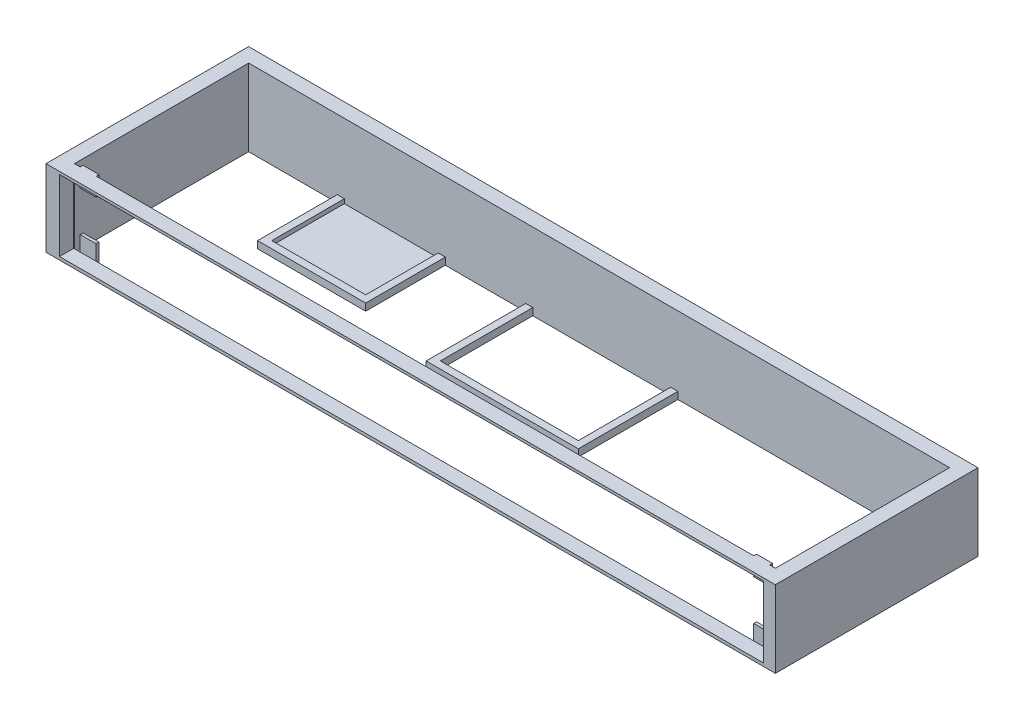
SolidWorks part; units mm, degrees
material "PLA"
ref_plane "Front Plane" through (0, 0, 0) normal (0, 0, 1) x (1, 0, 0)
ref_plane "Top Plane" through (0, 0, 0) normal (0, 1, 0) x (1, 0, 0)
ref_plane "Right Plane" through (0, 0, 0) normal (1, 0, 0) x (0, 0, -1)
sketch "Sketch2" plane through (0, 0, 0) normal (0, 1, 0) x (1, 0, 0)
  line L0 (0, -55) -> (0, 55) construction
  line L1 (-256.4, 71.4) -> (256.4, 71.4)
  line L2 (-256.4, 71.4) -> (-256.4, -71.08)
  line L3 (-256.4, -71.08) -> (256.4, -71.08)
  line L4 (256.4, 71.4) -> (256.4, -71.08)
  line L5 (-55, 0) -> (55, 0) construction
  dimension "D1" = 142.48
  dimension "D2" = 512.8
  dimension "D3" = 256.4
  dimension "D4" = 71.4
extrude "Extrude-Thin1" add sketch "Sketch2" along normal blind 54 thin contours L4 L3 L2 L1
sketch "Sketch3" plane through (0, 0, 71.08) normal (0, 0, 1) x (1, 0, 0)
  line L1 (-246.9323, 52.1414) -> (248.0677, 52.1414)
  line L2 (-246.9323, 52.1414) -> (-246.9323, 2.1414)
  line L3 (-246.9323, 2.1414) -> (248.0677, 2.1414)
  line L4 (248.0677, 52.1414) -> (248.0677, 2.1414)
  dimension "D1" = 50
  dimension "D2" = 495
extrude "Cut-Extrude1" cut sketch "Sketch3" against normal blind 10 contours L1 L4 L3 L2
sketch "Sketch4" plane through (0, 0, 61.08) normal (0, 0, -1) x (-1, 0, 0)
  line L0 (246.4, 54) -> (-246.4, 54) construction
  line L1 (242.3627, 54) -> (231.1637, 54)
  line L2 (242.3627, 54) -> (242.3627, 41.1714)
  line L3 (242.3627, 41.1714) -> (231.1637, 41.1714)
  line L4 (231.1637, 54) -> (231.1637, 41.1714)
extrude "Boss-Extrude1" add sketch "Sketch4" along normal blind 2
mirror "Mirror1" about plane through (0, 0, 0) normal (1, 0, 0) of "Boss-Extrude1"
ref_plane "Plane1" through (0, 27, 0) normal (0, 1, 0) x (1, 0, 0)
mirror "Mirror2" about plane through (0, 27, 0) normal (0, 1, 0) of "Boss-Extrude1"
mirror "Mirror3" about plane through (0, 27, 0) normal (0, 1, 0) of "Mirror1"
sketch "Sketch5" plane through (0, 0, -61.4) normal (0, 0, 1) x (1, 0, 0)
  line L1 (55.381, 0) -> (50.381, 0)
  line L2 (55.381, 0) -> (55.381, 5)
  line L3 (55.381, 5) -> (50.381, 5)
  line L4 (50.381, 0) -> (50.381, 5)
  dimension "D1" = 5
  dimension "D2" = 5
extrude "Boss-Extrude2" add sketch "Sketch5" along normal blind 70
sketch "Sketch7" plane through (50.381, 0, 0) normal (-1, 0, 0) x (0, 0, 1)
  line L0 (8.6, 0) -> (-61.4, 0) construction
  line L1 (8.6, 5) -> (3.6, 5)
  line L2 (8.6, 5) -> (8.6, 0)
  line L3 (8.6, 0) -> (3.6, 0)
  line L4 (3.6, 5) -> (3.6, 0)
  dimension "D1" = 5
extrude "Boss-Extrude3" add sketch "Sketch7" along normal blind 102
sketch "Sketch8" plane through (0, 0, 3.6) normal (0, 0, -1) x (-1, 0, 0)
  line L0 (51.619, 0) -> (-50.381, 0) construction
  line L1 (51.619, 5) -> (46.619, 5)
  line L2 (51.619, 5) -> (51.619, 0)
  line L3 (51.619, 0) -> (46.619, 0)
  line L4 (46.619, 5) -> (46.619, 0)
  dimension "D1" = 5
extrude "Boss-Extrude4" add sketch "Sketch8" along normal up to surface (65 mm away) up to face at (26.4405, 14.75, -61.4)
sketch "Sketch9" plane through (0, 0, -61.4) normal (0, 0, 1) x (1, 0, 0)
  line L0 (-246.4, 0) -> (-51.619, 0) construction
  line L1 (-108.1309, 0) -> (-113.1309, 0)
  line L2 (-108.1309, 0) -> (-108.1309, 5)
  line L3 (-108.1309, 5) -> (-113.1309, 5)
  line L4 (-113.1309, 0) -> (-113.1309, 5)
  dimension "D1" = 5
  dimension "D2" = 5
extrude "Boss-Extrude5" add sketch "Sketch9" along normal blind 56
sketch "Sketch10" plane through (-113.1309, 0, 0) normal (-1, 0, 0) x (0, 0, 1)
  line L0 (-5.4, 0) -> (-61.4, 0) construction
  line L1 (-5.4, 5) -> (-10.4, 5)
  line L2 (-5.4, 5) -> (-5.4, 0)
  line L3 (-5.4, 0) -> (-10.4, 0)
  line L4 (-10.4, 5) -> (-10.4, 0)
  dimension "D1" = 5
extrude "Boss-Extrude6" add sketch "Sketch10" along normal blind 71
sketch "Sketch11" plane through (0, 0, -10.4) normal (0, 0, -1) x (-1, 0, 0)
  line L0 (184.1309, 5) -> (113.1309, 5) construction
  line L1 (184.1309, 0) -> (179.1309, 0)
  line L2 (184.1309, 0) -> (184.1309, 5)
  line L3 (184.1309, 5) -> (179.1309, 5)
  line L4 (179.1309, 0) -> (179.1309, 5)
  dimension "D1" = 5
extrude "Boss-Extrude7" add sketch "Sketch11" along normal up to surface (51 mm away) up to face at (-26.7172, 8.625, -61.4)
sketch "Sketch14" plane through (-179.1309, 0, 0) normal (1, 0, 0) x (0, 0, -1)
  line L0 (10.4, 5) -> (10.4, 0) construction
  line L1 (61.4, 0) -> (10.4, 0)
  line L2 (61.4, 0) -> (61.4, 2)
  line L3 (61.4, 2) -> (10.4, 2)
  line L4 (10.4, 0) -> (10.4, 2)
  dimension "D1" = 2
extrude "Boss-Extrude8" add sketch "Sketch14" along normal up to surface (66 mm away) up to face at (-113.1309, 2.5, -35.9)
